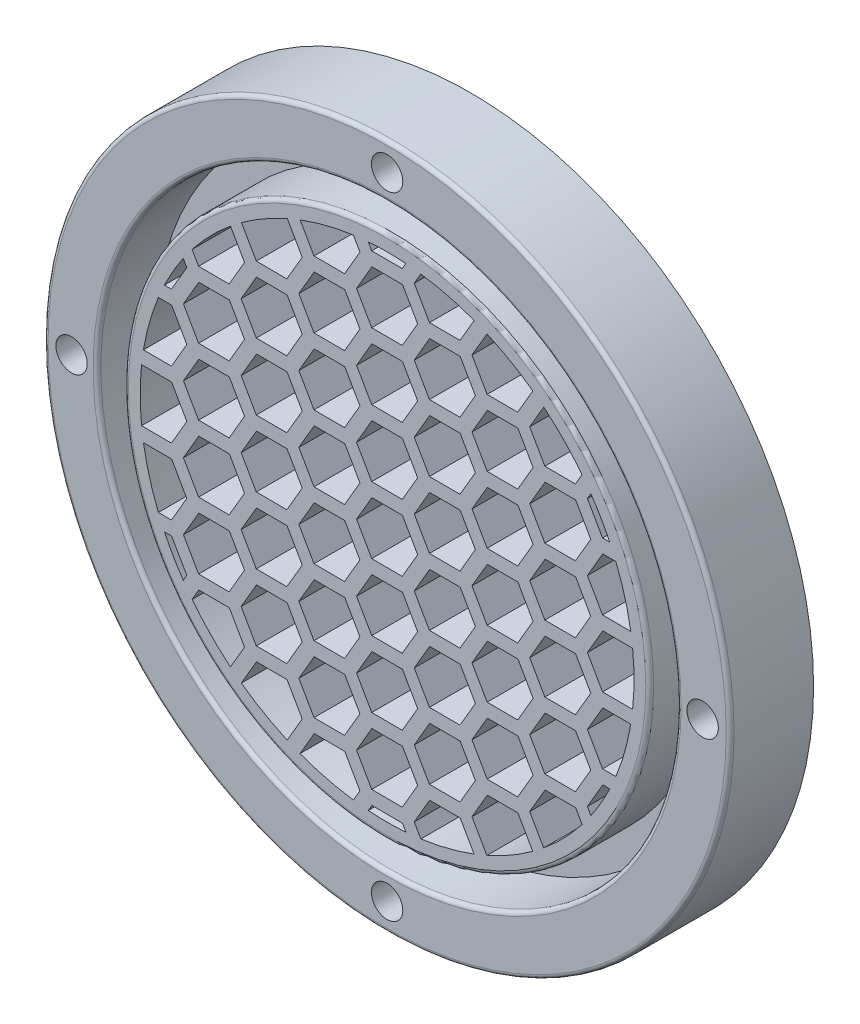
SolidWorks part; units mm, degrees
ref_plane "Ön Düzlem" through (0, 0, 0) normal (0, 0, 1) x (1, 0, 0)
ref_plane "Üst Düzlem" through (0, 0, 0) normal (0, 1, 0) x (1, 0, 0)
ref_plane "Sağ Düzlem" through (0, 0, 0) normal (1, 0, 0) x (0, 0, -1)
sketch "Çizim1" plane through (0, 0, 0) normal (0, 0, 1) x (1, 0, 0)
  circle A0 centre (0, 0) radius 87.5
  point P3 (-123.6118, 80.1463)
  dimension "D1" = 175
extrude "Yükseklik-Ekstrüzyon1" add sketch "Çizim1" along normal blind 21.3
sketch "Çizim2" plane through (0, 0, 21.3) normal (0, 0, 1) x (1, 0, 0)
  circle A0 centre (0, 0) radius 74
  circle A1 centre (0, 0) radius 67
  dimension "D1" = 148
  dimension "D2" = 134
extrude "Kes-Ekstrüzyon1" cut sketch "Çizim2" against normal blind 15
sketch "Çizim3" plane through (0, 0, 21.3) normal (0, 0, 1) x (1, 0, 0)
  circle A0 centre (0, 80.5) radius 4
  circle A1 centre (80.5, 0) radius 4
  circle A2 centre (0, -80.5) radius 4
  circle A3 centre (-80.5, 0) radius 4
  point P12 (0, 0)
  dimension "D1" = 8
  dimension "D2" = 80.5
  dimension "D3" = 4
extrude "Kes-Ekstrüzyon2" cut sketch "Çizim3" against normal blind 15
sketch "Çizim4" plane through (0, 0, 21.3) normal (0, 0, 1) x (1, 0, 0)
  circle A0 centre (0, 80.5) radius 2
  circle A1 centre (80.5, 0) radius 2
  circle A2 centre (0, -80.5) radius 2
  circle A3 centre (-80.5, 0) radius 2
  point P12 (0, 0)
  dimension "D1" = 4
  dimension "D2" = 4
extrude "Kes-Ekstrüzyon3" cut sketch "Çizim4" against normal blind 100
sketch "Çizim5" plane through (0, 0, 21.3) normal (0, 0, 1) x (1, 0, 0)
  line L0 (18.5895, 1.7327) -> (22.5166, 8.4653)
  line L1 (3.867, -6.7673) -> (7.7942, -0.0347)
  line L2 (7.7942, -0.0347) -> (3.9271, 6.7326)
  line L3 (3.9271, 6.7326) -> (-3.867, 6.7673)
  line L4 (-3.867, 6.7673) -> (-7.7942, 0.0347)
  line L5 (-7.7942, 0.0347) -> (-3.9271, -6.7326)
  line L6 (-3.9271, -6.7326) -> (3.867, -6.7673)
  line L7 (22.5166, 8.4653) -> (18.6496, 15.2326)
  line L8 (18.6496, 15.2326) -> (10.8554, 15.2673)
  line L9 (10.8554, 15.2673) -> (6.9283, 8.5347)
  line L10 (6.9283, 8.5347) -> (10.7953, 1.7674)
  line L11 (10.7953, 1.7674) -> (18.5895, 1.7327)
  line L12 (10.7953, -15.2326) -> (18.5895, -15.2673)
  line L13 (18.5895, -15.2673) -> (22.5166, -8.5347)
  line L14 (22.5166, -8.5347) -> (18.6496, -1.7674)
  line L15 (18.6496, -1.7674) -> (10.8554, -1.7327)
  line L16 (10.8554, -1.7327) -> (6.9283, -8.4653)
  line L17 (6.9283, -8.4653) -> (10.7953, -15.2326)
  line L18 (-7.7942, -16.9653) -> (-3.9271, -23.7326)
  line L19 (-3.9271, -23.7326) -> (3.867, -23.7673)
  line L20 (3.867, -23.7673) -> (7.7942, -17.0347)
  line L21 (7.7942, -17.0347) -> (3.9271, -10.2674)
  line L22 (3.9271, -10.2674) -> (-3.867, -10.2327)
  line L23 (-3.867, -10.2327) -> (-7.7942, -16.9653)
  line L24 (-18.5895, -1.7327) -> (-22.5166, -8.4653)
  line L25 (-22.5166, -8.4653) -> (-18.6496, -15.2326)
  line L26 (-18.6496, -15.2326) -> (-10.8554, -15.2673)
  line L27 (-10.8554, -15.2673) -> (-6.9283, -8.5347)
  line L28 (-6.9283, -8.5347) -> (-10.7953, -1.7674)
  line L29 (-10.7953, -1.7674) -> (-18.5895, -1.7327)
  line L30 (-10.7953, 15.2326) -> (-18.5895, 15.2673)
  line L31 (-18.5895, 15.2673) -> (-22.5166, 8.5347)
  line L32 (-22.5166, 8.5347) -> (-18.6496, 1.7674)
  line L33 (-18.6496, 1.7674) -> (-10.8554, 1.7327)
  line L34 (-10.8554, 1.7327) -> (-6.9283, 8.4653)
  line L35 (-6.9283, 8.4653) -> (-10.7953, 15.2326)
  line L36 (7.7942, 16.9653) -> (3.9271, 23.7326)
  line L37 (3.9271, 23.7326) -> (-3.867, 23.7673)
  line L38 (-3.867, 23.7673) -> (-7.7942, 17.0347)
  line L39 (-7.7942, 17.0347) -> (-3.9271, 10.2674)
  line L40 (-3.9271, 10.2674) -> (3.867, 10.2327)
  line L41 (3.867, 10.2327) -> (7.7942, 16.9653)
  line L42 (33.3119, 10.2327) -> (37.239, 16.9653)
  line L43 (37.239, 16.9653) -> (33.372, 23.7326)
  line L44 (33.372, 23.7326) -> (25.5778, 23.7673)
  line L45 (25.5778, 23.7673) -> (21.6507, 17.0347)
  line L46 (21.6507, 17.0347) -> (25.5177, 10.2674)
  line L47 (25.5177, 10.2674) -> (33.3119, 10.2327)
  line L48 (48.0343, 18.7327) -> (51.9614, 25.4653)
  line L49 (51.9614, 25.4653) -> (48.0944, 32.2326)
  line L50 (48.0944, 32.2326) -> (40.3003, 32.2673)
  line L51 (40.3003, 32.2673) -> (36.3731, 25.5347)
  line L52 (36.3731, 25.5347) -> (40.2402, 18.7674)
  line L53 (40.2402, 18.7674) -> (48.0343, 18.7327)
  line L57 (51.9942, 35.5753) -> (51.0956, 34.0347)
  line L58 (51.0956, 34.0347) -> (54.9626, 27.2674)
  line L59 (54.9626, 27.2674) -> (56.7973, 27.2593)
  line L60 (18.5895, 18.7327) -> (22.5166, 25.4653)
  line L61 (22.5166, 25.4653) -> (18.6496, 32.2326)
  line L62 (18.6496, 32.2326) -> (10.8554, 32.2673)
  line L63 (10.8554, 32.2673) -> (6.9283, 25.5347)
  line L64 (6.9283, 25.5347) -> (10.7953, 18.7674)
  line L65 (10.7953, 18.7674) -> (18.5895, 18.7327)
  line L66 (-10.7953, 32.2326) -> (-18.5895, 32.2673)
  line L67 (-18.5895, 32.2673) -> (-22.5166, 25.5347)
  line L68 (-22.5166, 25.5347) -> (-18.6496, 18.7674)
  line L69 (-18.6496, 18.7674) -> (-10.8554, 18.7327)
  line L70 (-10.8554, 18.7327) -> (-6.9283, 25.4653)
  line L71 (-6.9283, 25.4653) -> (-10.7953, 32.2326)
  line L72 (7.7942, 33.9653) -> (3.9271, 40.7326)
  line L73 (3.9271, 40.7326) -> (-3.867, 40.7673)
  line L74 (-3.867, 40.7673) -> (-7.7942, 34.0347)
  line L75 (-7.7942, 34.0347) -> (-3.9271, 27.2674)
  line L76 (-3.9271, 27.2674) -> (3.867, 27.2327)
  line L77 (3.867, 27.2327) -> (7.7942, 33.9653)
  line L78 (33.3119, 27.2327) -> (37.239, 33.9653)
  line L79 (37.239, 33.9653) -> (33.372, 40.7326)
  line L80 (33.372, 40.7326) -> (25.5778, 40.7673)
  line L81 (25.5778, 40.7673) -> (21.6507, 34.0347)
  line L82 (21.6507, 34.0347) -> (25.5177, 27.2674)
  line L83 (25.5177, 27.2674) -> (33.3119, 27.2327)
  line L84 (48.0343, 35.7327) -> (49.7425, 38.6612)
  line L87 (39.9684, 48.6983) -> (36.3731, 42.5347)
  line L88 (36.3731, 42.5347) -> (40.2402, 35.7674)
  line L89 (40.2402, 35.7674) -> (48.0343, 35.7327)
  line L90 (18.5895, 35.7327) -> (22.5166, 42.4653)
  line L91 (22.5166, 42.4653) -> (18.6496, 49.2326)
  line L92 (18.6496, 49.2326) -> (10.8554, 49.2673)
  line L93 (10.8554, 49.2673) -> (6.9283, 42.5347)
  line L94 (6.9283, 42.5347) -> (10.7953, 35.7674)
  line L95 (10.7953, 35.7674) -> (18.5895, 35.7327)
  line L96 (-10.7953, 49.2326) -> (-18.5895, 49.2673)
  line L97 (-18.5895, 49.2673) -> (-22.5166, 42.5347)
  line L98 (-22.5166, 42.5347) -> (-18.6496, 35.7674)
  line L99 (-18.6496, 35.7674) -> (-10.8554, 35.7327)
  line L100 (-10.8554, 35.7327) -> (-6.9283, 42.4653)
  line L101 (-6.9283, 42.4653) -> (-10.7953, 49.2326)
  line L102 (7.7942, 50.9653) -> (3.9271, 57.7326)
  line L103 (3.9271, 57.7326) -> (-3.867, 57.7673)
  line L104 (-3.867, 57.7673) -> (-7.7942, 51.0347)
  line L105 (-7.7942, 51.0347) -> (-3.9271, 44.2674)
  line L106 (-3.9271, 44.2674) -> (3.867, 44.2327)
  line L107 (3.867, 44.2327) -> (7.7942, 50.9653)
  line L108 (33.3119, 44.2327) -> (37.1779, 50.8606)
  line L111 (25.4883, 57.6138) -> (21.6507, 51.0347)
  line L112 (21.6507, 51.0347) -> (25.5177, 44.2674)
  line L113 (25.5177, 44.2674) -> (33.3119, 44.2327)
  line L120 (18.5895, 52.7327) -> (22.2174, 58.9524)
  line L123 (8.6052, 62.4095) -> (6.9283, 59.5347)
  line L124 (6.9283, 59.5347) -> (10.7953, 52.7674)
  line L125 (10.7953, 52.7674) -> (18.5895, 52.7327)
  line L128 (-22.1898, 58.9628) -> (-18.6496, 52.7674)
  line L129 (-18.6496, 52.7674) -> (-10.8554, 52.7327)
  line L130 (-10.8554, 52.7327) -> (-6.9283, 59.4653)
  line L131 (-6.9283, 59.4653) -> (-8.6103, 62.4088)
  line L135 (-4.812, 62.816) -> (-3.9271, 61.2674)
  line L136 (-3.9271, 61.2674) -> (3.867, 61.2327)
  line L137 (3.867, 61.2327) -> (4.7914, 62.8175)
  line L150 (-18.5895, 66.2673) -> (-22.5166, 59.5347) [skipped]
  line L151 (-10.7953, 66.2326) -> (-18.5895, 66.2673) [skipped]
  line L152 (-3.867, 74.7673) -> (-7.7942, 68.0347) [skipped]
  line L153 (3.9271, 74.7326) -> (-3.867, 74.7673) [skipped]
  line L154 (7.7942, 67.9653) -> (3.9271, 74.7326) [skipped]
  line L155 (22.5166, 59.4653) -> (18.6496, 66.2326) [skipped]
  line L156 (21.6507, 68.0347) -> (25.5177, 61.2674) [skipped]
  line L157 (18.6496, 66.2326) -> (10.8554, 66.2673) [skipped]
  line L158 (33.372, 74.7326) -> (25.5778, 74.7673) [skipped]
  line L159 (25.5778, 74.7673) -> (21.6507, 68.0347) [skipped]
  line L160 (37.239, 67.9653) -> (33.372, 74.7326) [skipped]
  line L161 (36.3731, 76.5347) -> (40.2402, 69.7674) [skipped]
  line L162 (48.0944, 83.2326) -> (40.3003, 83.2673) [skipped]
  line L163 (48.0343, 69.7327) -> (51.9614, 76.4653) [skipped]
  line L164 (51.9614, 76.4653) -> (48.0944, 83.2326) [skipped]
  line L165 (40.3003, 83.2673) -> (36.3731, 76.5347) [skipped]
  line L166 (48.0944, 66.2326) -> (40.3003, 66.2673) [skipped]
  line L167 (48.0343, 52.7327) -> (51.9614, 59.4653) [skipped]
  line L168 (40.2402, 52.7674) -> (48.0343, 52.7327) [skipped]
  line L169 (51.9614, 42.4653) -> (48.0944, 49.2326) [skipped]
  line L170 (62.8169, 40.7326) -> (55.0227, 40.7673) [skipped]
  line L171 (62.7567, 27.2327) -> (66.6839, 33.9653) [skipped]
  line L172 (66.6839, 33.9653) -> (62.8169, 40.7326) [skipped]
  line L173 (48.0944, 49.2326) -> (40.3003, 49.2673) [skipped]
  line L174 (40.3003, 66.2673) -> (36.3731, 59.5347) [skipped]
  line L175 (33.3119, 61.2327) -> (37.239, 67.9653) [skipped]
  line L176 (25.5177, 61.2674) -> (33.3119, 61.2327) [skipped]
  line L177 (40.2402, 69.7674) -> (48.0343, 69.7327) [skipped]
  line L178 (51.9614, 59.4653) -> (48.0944, 66.2326) [skipped]
  line L179 (36.3731, 59.5347) -> (40.2402, 52.7674) [skipped]
  line L180 (37.239, 50.9653) -> (33.372, 57.7326) [skipped]
  line L181 (33.372, 57.7326) -> (25.5778, 57.7673) [skipped]
  line L182 (-25.5177, 23.7326) -> (-33.3119, 23.7673)
  line L183 (-33.3119, 23.7673) -> (-37.239, 17.0347)
  line L184 (-37.239, 17.0347) -> (-33.372, 10.2674)
  line L185 (-33.372, 10.2674) -> (-25.5778, 10.2327)
  line L186 (-25.5778, 10.2327) -> (-21.6507, 16.9653)
  line L187 (-21.6507, 16.9653) -> (-25.5177, 23.7326)
  line L188 (-25.5177, 40.7326) -> (-33.3119, 40.7673)
  line L189 (-33.3119, 40.7673) -> (-37.239, 34.0347)
  line L190 (-37.239, 34.0347) -> (-33.372, 27.2674)
  line L191 (-33.372, 27.2674) -> (-25.5778, 27.2327)
  line L192 (-25.5778, 27.2327) -> (-21.6507, 33.9653)
  line L193 (-21.6507, 33.9653) -> (-25.5177, 40.7326)
  line L196 (-37.1508, 50.8804) -> (-33.372, 44.2674)
  line L197 (-33.372, 44.2674) -> (-25.5778, 44.2327)
  line L198 (-25.5778, 44.2327) -> (-21.6507, 50.9653)
  line L199 (-21.6507, 50.9653) -> (-25.4576, 57.6273)
  line L200 (-33.3119, 6.7673) -> (-37.239, 0.0347)
  line L201 (-37.239, 0.0347) -> (-33.372, -6.7326)
  line L202 (-33.372, -6.7326) -> (-25.5778, -6.7673)
  line L203 (-25.5778, -6.7673) -> (-21.6507, -0.0347)
  line L204 (-21.6507, -0.0347) -> (-25.5177, 6.7326)
  line L205 (-25.5177, 6.7326) -> (-33.3119, 6.7673)
  line L206 (-40.2402, 32.2326) -> (-48.0343, 32.2673)
  line L207 (-48.0343, 32.2673) -> (-51.9614, 25.5347)
  line L208 (-51.9614, 25.5347) -> (-48.0944, 18.7674)
  line L209 (-48.0944, 18.7674) -> (-40.3003, 18.7327)
  line L210 (-40.3003, 18.7327) -> (-36.3731, 25.4653)
  line L211 (-36.3731, 25.4653) -> (-40.2402, 32.2326)
  line L214 (-49.7457, 38.6571) -> (-48.0944, 35.7674)
  line L215 (-48.0944, 35.7674) -> (-40.3003, 35.7327)
  line L216 (-40.3003, 35.7327) -> (-36.3731, 42.4653)
  line L217 (-36.3731, 42.4653) -> (-39.9456, 48.7171)
  line L224 (-48.0343, 15.2673) -> (-51.9614, 8.5347)
  line L225 (-51.9614, 8.5347) -> (-48.0944, 1.7674)
  line L226 (-48.0944, 1.7674) -> (-40.3003, 1.7327)
  line L227 (-40.3003, 1.7327) -> (-36.3731, 8.4653)
  line L228 (-36.3731, 8.4653) -> (-40.2402, 15.2326)
  line L229 (-40.2402, 15.2326) -> (-48.0343, 15.2673)
  line L233 (-56.8062, 27.2407) -> (-55.0227, 27.2327)
  line L234 (-55.0227, 27.2327) -> (-51.0956, 33.9653)
  line L235 (-51.0956, 33.9653) -> (-52.0059, 35.5583)
  line L250 (-62.1582, 10.2645) -> (-55.0227, 10.2327)
  line L251 (-55.0227, 10.2327) -> (-51.0956, 16.9653)
  line L252 (-51.0956, 16.9653) -> (-54.9626, 23.7326)
  line L253 (-54.9626, 23.7326) -> (-58.3528, 23.7477)
  line L254 (-25.5177, 57.7326) -> (-33.3119, 57.7673) [skipped]
  line L255 (-33.3119, 57.7673) -> (-37.239, 51.0347) [skipped]
  line L256 (-40.3003, 52.7327) -> (-36.3731, 59.4653) [skipped]
  line L257 (-48.0944, 52.7674) -> (-40.3003, 52.7327) [skipped]
  line L258 (-40.2402, 49.2326) -> (-48.0343, 49.2673) [skipped]
  line L259 (-48.0343, 49.2673) -> (-51.9614, 42.5347) [skipped]
  line L260 (-62.7567, 23.7673) -> (-66.6839, 17.0347) [skipped]
  line L261 (-66.6839, 34.0347) -> (-62.8169, 27.2674) [skipped]
  line L262 (-54.9626, 40.7326) -> (-62.7567, 40.7673) [skipped]
  line L263 (-62.8169, 44.2674) -> (-55.0227, 44.2327) [skipped]
  line L264 (-62.7567, 40.7673) -> (-66.6839, 34.0347) [skipped]
  line L265 (-66.6839, 51.0347) -> (-62.8169, 44.2674) [skipped]
  line L266 (-54.9626, 57.7326) -> (-62.7567, 57.7673) [skipped]
  line L267 (-51.9614, 59.5347) -> (-48.0944, 52.7674) [skipped]
  line L268 (-48.0343, 66.2673) -> (-51.9614, 59.5347) [skipped]
  line L269 (-51.0956, 50.9653) -> (-54.9626, 57.7326) [skipped]
  line L270 (-55.0227, 44.2327) -> (-51.0956, 50.9653) [skipped]
  line L271 (-62.7567, 57.7673) -> (-66.6839, 51.0347) [skipped]
  line L272 (-66.6839, 68.0347) -> (-62.8169, 61.2674) [skipped]
  line L273 (-62.7567, 74.7673) -> (-66.6839, 68.0347) [skipped]
  line L274 (-54.9626, 74.7326) -> (-62.7567, 74.7673) [skipped]
  line L275 (-51.0956, 67.9653) -> (-54.9626, 74.7326) [skipped]
  line L276 (-62.8169, 61.2674) -> (-55.0227, 61.2327) [skipped]
  line L277 (-55.0227, 61.2327) -> (-51.0956, 67.9653) [skipped]
  line L278 (-40.2402, 66.2326) -> (-48.0343, 66.2673) [skipped]
  line L279 (-36.3731, 59.4653) -> (-40.2402, 66.2326) [skipped]
  line L280 (-66.6839, 17.0347) -> (-62.8169, 10.2674) [skipped]
  line L283 (-62.6391, -6.7334) -> (-55.0227, -6.7673)
  line L284 (-55.0227, -6.7673) -> (-51.0956, -0.0347)
  line L285 (-51.0956, -0.0347) -> (-54.9626, 6.7326)
  line L286 (-54.9626, 6.7326) -> (-62.6355, 6.7667)
  line L287 (-48.0343, -1.7327) -> (-51.9614, -8.4653)
  line L288 (-51.9614, -8.4653) -> (-48.0944, -15.2326)
  line L289 (-48.0944, -15.2326) -> (-40.3003, -15.2673)
  line L290 (-40.3003, -15.2673) -> (-36.3731, -8.5347)
  line L291 (-36.3731, -8.5347) -> (-40.2402, -1.7674)
  line L292 (-40.2402, -1.7674) -> (-48.0343, -1.7327)
  line L293 (-33.3119, -10.2327) -> (-37.239, -16.9653)
  line L294 (-37.239, -16.9653) -> (-33.372, -23.7326)
  line L295 (-33.372, -23.7326) -> (-25.5778, -23.7673)
  line L296 (-25.5778, -23.7673) -> (-21.6507, -17.0347)
  line L297 (-21.6507, -17.0347) -> (-25.5177, -10.2674)
  line L298 (-25.5177, -10.2674) -> (-33.3119, -10.2327)
  line L299 (-22.5166, -25.4653) -> (-18.6496, -32.2326)
  line L300 (-18.6496, -32.2326) -> (-10.8554, -32.2673)
  line L301 (-10.8554, -32.2673) -> (-6.9283, -25.5347)
  line L302 (-6.9283, -25.5347) -> (-10.7953, -18.7674)
  line L303 (-10.7953, -18.7674) -> (-18.5895, -18.7327)
  line L304 (-18.5895, -18.7327) -> (-22.5166, -25.4653)
  line L313 (-58.3508, -23.7525) -> (-55.0227, -23.7673)
  line L314 (-55.0227, -23.7673) -> (-51.0956, -17.0347)
  line L315 (-51.0956, -17.0347) -> (-54.9626, -10.2674)
  line L316 (-54.9626, -10.2674) -> (-62.163, -10.2354)
  line L317 (-48.0343, -18.7327) -> (-51.9614, -25.4653)
  line L318 (-51.9614, -25.4653) -> (-48.0944, -32.2326)
  line L319 (-48.0944, -32.2326) -> (-40.3003, -32.2673)
  line L320 (-40.3003, -32.2673) -> (-36.3731, -25.5347)
  line L321 (-36.3731, -25.5347) -> (-40.2402, -18.7674)
  line L322 (-40.2402, -18.7674) -> (-48.0343, -18.7327)
  line L323 (-37.239, -33.9653) -> (-33.372, -40.7326)
  line L324 (-33.372, -40.7326) -> (-25.5778, -40.7673)
  line L325 (-25.5778, -40.7673) -> (-21.6507, -34.0347)
  line L326 (-21.6507, -34.0347) -> (-25.5177, -27.2674)
  line L327 (-25.5177, -27.2674) -> (-33.3119, -27.2327)
  line L328 (-33.3119, -27.2327) -> (-37.239, -33.9653)
  line L344 (-51.9942, -35.5753) -> (-51.0956, -34.0347)
  line L345 (-51.0956, -34.0347) -> (-54.9626, -27.2674)
  line L346 (-54.9626, -27.2674) -> (-56.7973, -27.2593)
  line L349 (-39.9684, -48.6983) -> (-36.3731, -42.5347)
  line L350 (-36.3731, -42.5347) -> (-40.2402, -35.7674)
  line L351 (-40.2402, -35.7674) -> (-48.0343, -35.7327)
  line L352 (-48.0343, -35.7327) -> (-49.7425, -38.6612)
  line L353 (-65.818, -8.5347) -> (-69.685, -1.7674) [skipped]
  line L354 (-66.6839, 0.0347) -> (-62.8169, -6.7326) [skipped]
  line L355 (-62.7567, 6.7673) -> (-66.6839, 0.0347) [skipped]
  line L356 (-62.7567, -10.2327) -> (-66.6839, -16.9653) [skipped]
  line L357 (-48.0944, -49.2326) -> (-40.3003, -49.2673) [skipped]
  line L358 (-51.9614, -42.4653) -> (-48.0944, -49.2326) [skipped]
  line L359 (-62.8169, -40.7326) -> (-55.0227, -40.7673) [skipped]
  line L360 (-62.7567, -27.2327) -> (-66.6839, -33.9653) [skipped]
  line L361 (-66.6839, -33.9653) -> (-62.8169, -40.7326) [skipped]
  line L362 (-69.7451, -32.2673) -> (-65.818, -25.5347) [skipped]
  line L363 (-65.818, -25.5347) -> (-69.685, -18.7674) [skipped]
  line L364 (-66.6839, -16.9653) -> (-62.8169, -23.7326) [skipped]
  line L365 (-69.7451, -15.2673) -> (-65.818, -8.5347) [skipped]
  line L366 (-77.4792, -1.7327) -> (-81.4063, -8.4653) [skipped]
  line L367 (-69.685, -1.7674) -> (-77.4792, -1.7327) [skipped]
  line L368 (-77.5393, -15.2326) -> (-69.7451, -15.2673) [skipped]
  line L369 (-69.685, -18.7674) -> (-77.4792, -18.7327) [skipped]
  line L370 (-77.4792, -18.7327) -> (-81.4063, -25.4653) [skipped]
  line L371 (-84.4676, -23.7673) -> (-80.5404, -17.0347) [skipped]
  line L372 (-84.4075, -10.2674) -> (-92.2016, -10.2327) [skipped]
  line L373 (-80.5404, -17.0347) -> (-84.4075, -10.2674) [skipped]
  line L374 (-92.2617, -23.7326) -> (-84.4676, -23.7673) [skipped]
  line L375 (-81.4063, -8.4653) -> (-77.5393, -15.2326) [skipped]
  line L376 (-96.1287, -16.9653) -> (-92.2617, -23.7326) [skipped]
  line L377 (-92.2016, -10.2327) -> (-96.1287, -16.9653) [skipped]
  line L378 (-77.5393, -32.2326) -> (-69.7451, -32.2673) [skipped]
  line L379 (-81.4063, -25.4653) -> (-77.5393, -32.2326) [skipped]
  line L380 (25.5177, -23.7326) -> (33.3119, -23.7673)
  line L381 (33.3119, -23.7673) -> (37.239, -17.0347)
  line L382 (37.239, -17.0347) -> (33.372, -10.2674)
  line L383 (33.372, -10.2674) -> (25.5778, -10.2327)
  line L384 (25.5778, -10.2327) -> (21.6507, -16.9653)
  line L385 (21.6507, -16.9653) -> (25.5177, -23.7326)
  line L386 (48.0343, 1.7327) -> (51.9614, 8.4653)
  line L387 (51.9614, 8.4653) -> (48.0944, 15.2326)
  line L388 (48.0944, 15.2326) -> (40.3003, 15.2673)
  line L389 (40.3003, 15.2673) -> (36.3731, 8.5347)
  line L390 (36.3731, 8.5347) -> (40.2402, 1.7674)
  line L391 (40.2402, 1.7674) -> (48.0343, 1.7327)
  line L392 (33.3119, -6.7673) -> (37.239, -0.0347)
  line L393 (37.239, -0.0347) -> (33.372, 6.7326)
  line L394 (33.372, 6.7326) -> (25.5778, 6.7673)
  line L395 (25.5778, 6.7673) -> (21.6507, 0.0347)
  line L396 (21.6507, 0.0347) -> (25.5177, -6.7326)
  line L397 (25.5177, -6.7326) -> (33.3119, -6.7673)
  line L400 (58.3508, 23.7525) -> (55.0227, 23.7673)
  line L401 (55.0227, 23.7673) -> (51.0956, 17.0347)
  line L402 (51.0956, 17.0347) -> (54.9626, 10.2674)
  line L403 (54.9626, 10.2674) -> (62.163, 10.2354)
  line L404 (6.9283, -25.4653) -> (10.7953, -32.2326)
  line L405 (10.7953, -32.2326) -> (18.5895, -32.2673)
  line L406 (18.5895, -32.2673) -> (22.5166, -25.5347)
  line L407 (22.5166, -25.5347) -> (18.6496, -18.7674)
  line L408 (18.6496, -18.7674) -> (10.8554, -18.7327)
  line L409 (10.8554, -18.7327) -> (6.9283, -25.4653)
  line L410 (-7.7942, -33.9653) -> (-3.9271, -40.7326)
  line L411 (-3.9271, -40.7326) -> (3.867, -40.7673)
  line L412 (3.867, -40.7673) -> (7.7942, -34.0347)
  line L413 (7.7942, -34.0347) -> (3.9271, -27.2674)
  line L414 (3.9271, -27.2674) -> (-3.867, -27.2327)
  line L415 (-3.867, -27.2327) -> (-7.7942, -33.9653)
  line L416 (-22.5166, -42.4653) -> (-18.6496, -49.2326)
  line L417 (-18.6496, -49.2326) -> (-10.8554, -49.2673)
  line L418 (-10.8554, -49.2673) -> (-6.9283, -42.5347)
  line L419 (-6.9283, -42.5347) -> (-10.7953, -35.7674)
  line L420 (-10.7953, -35.7674) -> (-18.5895, -35.7327)
  line L421 (-18.5895, -35.7327) -> (-22.5166, -42.4653)
  line L422 (40.2402, -32.2326) -> (48.0343, -32.2673)
  line L423 (48.0343, -32.2673) -> (51.9614, -25.5347)
  line L424 (51.9614, -25.5347) -> (48.0944, -18.7674)
  line L425 (48.0944, -18.7674) -> (40.3003, -18.7327)
  line L426 (40.3003, -18.7327) -> (36.3731, -25.4653)
  line L427 (36.3731, -25.4653) -> (40.2402, -32.2326)
  line L430 (62.6391, 6.7334) -> (55.0227, 6.7673)
  line L431 (55.0227, 6.7673) -> (51.0956, 0.0347)
  line L432 (51.0956, 0.0347) -> (54.9626, -6.7326)
  line L433 (54.9626, -6.7326) -> (62.6355, -6.7667)
  line L434 (48.0343, -15.2673) -> (51.9614, -8.5347)
  line L435 (51.9614, -8.5347) -> (48.0944, -1.7674)
  line L436 (48.0944, -1.7674) -> (40.3003, -1.7327)
  line L437 (40.3003, -1.7327) -> (36.3731, -8.4653)
  line L438 (36.3731, -8.4653) -> (40.2402, -15.2326)
  line L439 (40.2402, -15.2326) -> (48.0343, -15.2673)
  line L446 (21.6507, -33.9653) -> (25.5177, -40.7326)
  line L447 (25.5177, -40.7326) -> (33.3119, -40.7673)
  line L448 (33.3119, -40.7673) -> (37.239, -34.0347)
  line L449 (37.239, -34.0347) -> (33.372, -27.2674)
  line L450 (33.372, -27.2674) -> (25.5778, -27.2327)
  line L451 (25.5778, -27.2327) -> (21.6507, -33.9653)
  line L452 (6.9283, -42.4653) -> (10.7953, -49.2326)
  line L453 (10.7953, -49.2326) -> (18.5895, -49.2673)
  line L454 (18.5895, -49.2673) -> (22.5166, -42.5347)
  line L455 (22.5166, -42.5347) -> (18.6496, -35.7674)
  line L456 (18.6496, -35.7674) -> (10.8554, -35.7327)
  line L457 (10.8554, -35.7327) -> (6.9283, -42.4653)
  line L458 (-7.7942, -50.9653) -> (-3.9271, -57.7326)
  line L459 (-3.9271, -57.7326) -> (3.867, -57.7673)
  line L460 (3.867, -57.7673) -> (7.7942, -51.0347)
  line L461 (7.7942, -51.0347) -> (3.9271, -44.2674)
  line L462 (3.9271, -44.2674) -> (-3.867, -44.2327)
  line L463 (-3.867, -44.2327) -> (-7.7942, -50.9653)
  line L467 (56.8062, -27.2407) -> (55.0227, -27.2327)
  line L468 (55.0227, -27.2327) -> (51.0956, -33.9653)
  line L469 (51.0956, -33.9653) -> (52.0059, -35.5583)
  line L478 (62.1582, -10.2645) -> (55.0227, -10.2327)
  line L479 (55.0227, -10.2327) -> (51.0956, -16.9653)
  line L480 (51.0956, -16.9653) -> (54.9626, -23.7326)
  line L481 (54.9626, -23.7326) -> (58.3528, -23.7477)
  line L488 (36.3731, -42.4653) -> (39.9456, -48.7171)
  line L491 (49.7457, -38.6571) -> (48.0944, -35.7674)
  line L492 (48.0944, -35.7674) -> (40.3003, -35.7327)
  line L493 (40.3003, -35.7327) -> (36.3731, -42.4653)
  line L494 (21.6507, -50.9653) -> (25.4576, -57.6273)
  line L497 (37.1508, -50.8804) -> (33.372, -44.2674)
  line L498 (33.372, -44.2674) -> (25.5778, -44.2327)
  line L499 (25.5778, -44.2327) -> (21.6507, -50.9653)
  line L500 (6.9283, -59.4653) -> (8.6103, -62.4088)
  line L503 (22.1898, -58.9628) -> (18.6496, -52.7674)
  line L504 (18.6496, -52.7674) -> (10.8554, -52.7327)
  line L505 (10.8554, -52.7327) -> (6.9283, -59.4653)
  line L508 (-25.4883, -57.6138) -> (-21.6507, -51.0347)
  line L509 (-21.6507, -51.0347) -> (-25.5177, -44.2674)
  line L510 (-25.5177, -44.2674) -> (-33.3119, -44.2327)
  line L511 (-33.3119, -44.2327) -> (-37.1779, -50.8606)
  line L514 (-8.6052, -62.4095) -> (-6.9283, -59.5347)
  line L515 (-6.9283, -59.5347) -> (-10.7953, -52.7674)
  line L516 (-10.7953, -52.7674) -> (-18.5895, -52.7327)
  line L517 (-18.5895, -52.7327) -> (-22.2174, -58.9524)
  line L521 (4.812, -62.816) -> (3.9271, -61.2674)
  line L522 (3.9271, -61.2674) -> (-3.867, -61.2327)
  line L523 (-3.867, -61.2327) -> (-4.7914, -62.8175)
  line L524 (-37.239, -50.9653) -> (-33.372, -57.7326) [skipped]
  line L525 (-33.372, -57.7326) -> (-25.5778, -57.7673) [skipped]
  line L526 (-22.5166, -59.4653) -> (-18.6496, -66.2326) [skipped]
  line L527 (-18.6496, -66.2326) -> (-10.8554, -66.2673) [skipped]
  line L529 (-7.7942, -67.9653) -> (-3.9271, -74.7326) [skipped]
  line L531 (18.5895, -66.2673) -> (22.5166, -59.5347) [skipped]
  line L532 (10.7953, -66.2326) -> (18.5895, -66.2673) [skipped]
  line L533 (25.5177, -57.7326) -> (33.3119, -57.7673) [skipped]
  line L534 (33.3119, -57.7673) -> (37.239, -51.0347) [skipped]
  line L535 (40.2402, -49.2326) -> (48.0343, -49.2673) [skipped]
  line L536 (48.0343, -49.2673) -> (51.9614, -42.5347) [skipped]
  line L537 (54.9626, -40.7326) -> (62.7567, -40.7673) [skipped]
  line L538 (62.7567, -40.7673) -> (66.6839, -34.0347) [skipped]
  line L539 (66.6839, -34.0347) -> (62.8169, -27.2674) [skipped]
  line L540 (62.7567, -23.7673) -> (66.6839, -17.0347) [skipped]
  line L541 (66.6839, -17.0347) -> (62.8169, -10.2674) [skipped]
  line L542 (62.7567, -6.7673) -> (66.6839, -0.0347) [skipped]
  line L543 (66.6839, -0.0347) -> (62.8169, 6.7326) [skipped]
  line L544 (65.818, 8.5347) -> (69.685, 1.7674) [skipped]
  line L545 (69.7451, 15.2673) -> (65.818, 8.5347) [skipped]
  line L546 (62.7567, 10.2327) -> (66.6839, 16.9653) [skipped]
  line L547 (66.6839, 16.9653) -> (62.8169, 23.7326) [skipped]
  line L548 (77.5393, 15.2326) -> (69.7451, 15.2673) [skipped]
  line L549 (69.685, 1.7674) -> (77.4792, 1.7327) [skipped]
  line L550 (77.5393, -1.7674) -> (69.7451, -1.7327) [skipped]
  line L551 (69.685, -15.2326) -> (77.4792, -15.2673) [skipped]
  line L552 (65.818, -8.4653) -> (69.685, -15.2326) [skipped]
  line L553 (69.7451, -1.7327) -> (65.818, -8.4653) [skipped]
  line L554 (81.4063, -8.5347) -> (77.5393, -1.7674) [skipped]
  line L555 (80.5404, 0.0347) -> (84.4075, -6.7326) [skipped]
  line L556 (92.2617, 6.7326) -> (84.4676, 6.7673) [skipped]
  line L557 (96.1287, -0.0347) -> (92.2617, 6.7326) [skipped]
  line L558 (84.4075, -6.7326) -> (92.2016, -6.7673) [skipped]
  line L559 (92.2016, -6.7673) -> (96.1287, -0.0347) [skipped]
  line L560 (77.4792, -15.2673) -> (81.4063, -8.5347) [skipped]
  line L561 (77.4792, 1.7327) -> (81.4063, 8.4653) [skipped]
  line L562 (84.4676, 6.7673) -> (80.5404, 0.0347) [skipped]
  line L563 (81.4063, 8.4653) -> (77.5393, 15.2326) [skipped]
  circle A0 centre (0, 0) radius 6.75 construction
  arc A1 (-58.3528, 23.7477) -> (-62.1582, 10.2645) centre (0, 0) ccw
  arc A2 (-52.0059, 35.5583) -> (-56.8062, 27.2407) centre (0, 0) ccw
  arc A3 (-39.9456, 48.7171) -> (-49.7457, 38.6571) centre (0, 0) ccw
  arc A4 (-25.4576, 57.6273) -> (-37.1508, 50.8804) centre (0, 0) ccw
  arc A5 (-8.6103, 62.4088) -> (-22.1898, 58.9628) centre (0, 0) ccw
  arc A6 (4.7914, 62.8175) -> (-4.812, 62.816) centre (0, 0) ccw
  arc A7 (22.2174, 58.9524) -> (8.6052, 62.4095) centre (0, 0) ccw
  arc A8 (37.1779, 50.8606) -> (25.4883, 57.6138) centre (0, 0) ccw
  arc A9 (49.7425, 38.6612) -> (39.9684, 48.6983) centre (0, 0) ccw
  arc A10 (56.7973, 27.2593) -> (51.9942, 35.5753) centre (0, 0) ccw
  arc A11 (62.163, 10.2354) -> (58.3508, 23.7525) centre (0, 0) ccw
  arc A12 (62.6355, -6.7667) -> (62.6391, 6.7334) centre (0, 0) ccw
  arc A13 (58.3528, -23.7477) -> (62.1582, -10.2645) centre (0, 0) ccw
  arc A14 (52.0059, -35.5583) -> (56.8062, -27.2407) centre (0, 0) ccw
  arc A15 (39.9456, -48.7171) -> (49.7457, -38.6571) centre (0, 0) ccw
  arc A16 (25.4576, -57.6273) -> (37.1508, -50.8804) centre (0, 0) ccw
  arc A17 (8.6103, -62.4088) -> (22.1898, -58.9628) centre (0, 0) ccw
  arc A18 (-4.7914, -62.8175) -> (4.812, -62.816) centre (0, 0) ccw
  arc A19 (-22.2174, -58.9524) -> (-8.6052, -62.4095) centre (0, 0) ccw
  arc A20 (-37.1779, -50.8606) -> (-25.4883, -57.6138) centre (0, 0) ccw
  arc A21 (-49.7425, -38.6612) -> (-39.9684, -48.6983) centre (0, 0) ccw
  arc A22 (-56.7973, -27.2593) -> (-51.9942, -35.5753) centre (0, 0) ccw
  arc A23 (-62.163, -10.2354) -> (-58.3508, -23.7525) centre (0, 0) ccw
  arc A24 (-62.6355, 6.7667) -> (-62.6391, -6.7334) centre (0, 0) ccw
  point P49 (0, 0)
  dimension "D1" = 2
  dimension "D3" = 4
  dimension "D4" = 4
  dimension "D5" = 4
  dimension "D6" = 4
  dimension "D7" = 4
  dimension "D8" = 2
  dimension "D2" = 6
extrude "Kes-Ekstrüzyon4" cut sketch "Çizim5" against normal blind 100
sketch "Çizim6" plane through (0, 0, 0) normal (0, 0, -1) x (-1, 0, 0)
  arc A0 (-2.9032, 85.7509) -> (-85.7509, 2.9032) centre (0, 0) ccw
  arc A2 (-2.8945, 75.2443) -> (-75.2443, 2.8945) centre (0, 0) ccw
  arc A3 (-2.9032, 85.7509) -> (-2.8945, 75.2443) centre (0, 80.5) ccw
  arc A4 (75.2443, -2.8945) -> (85.7509, -2.9032) centre (80.5, 0) ccw
  arc A5 (-2.8945, -75.2443) -> (-2.9032, -85.7509) centre (0, -80.5) ccw
  arc A6 (-75.2443, 2.8945) -> (-85.7509, 2.9032) centre (-80.5, 0) ccw
  arc A7 (2.8945, 75.2443) -> (2.9032, 85.7509) centre (0, 80.5) ccw
  arc A8 (-75.2443, -2.8945) -> (-2.8945, -75.2443) centre (0, 0) ccw
  arc A9 (-85.7509, -2.9032) -> (-2.9032, -85.7509) centre (0, 0) ccw
  arc A10 (-85.7509, -2.9032) -> (-75.2443, -2.8945) centre (-80.5, 0) ccw
  arc A11 (2.8945, -75.2443) -> (75.2443, -2.8945) centre (0, 0) ccw
  arc A12 (2.9032, -85.7509) -> (85.7509, -2.9032) centre (0, 0) ccw
  arc A13 (2.9032, -85.7509) -> (2.8945, -75.2443) centre (0, -80.5) ccw
  arc A14 (75.2443, 2.8945) -> (2.8945, 75.2443) centre (0, 0) ccw
  arc A15 (85.7509, 2.9032) -> (2.9032, 85.7509) centre (0, 0) ccw
  arc A16 (85.7509, 2.9032) -> (75.2443, 2.8945) centre (80.5, 0) ccw
  point P16 (0, 0)
  dimension "D1" = 171.6
  dimension "D2" = 150.6
  dimension "D3" = 12
  dimension "D4" = 4
extrude "Kes-Ekstrüzyon5" cut sketch "Çizim6" against normal blind 19
sketch "Çizim7" plane through (0, 0, 0) normal (0, 0, -1) x (-1, 0, 0)
  circle A0 centre (0, 0) radius 85.8
extrude "Kes-Ekstrüzyon7" cut sketch "Çizim7" against normal blind 6
fillet "Radyus2" radius 1 3 edges at (67, 0, 21.3) (87.5, 0, 21.3) (74, 0, 21.3)
